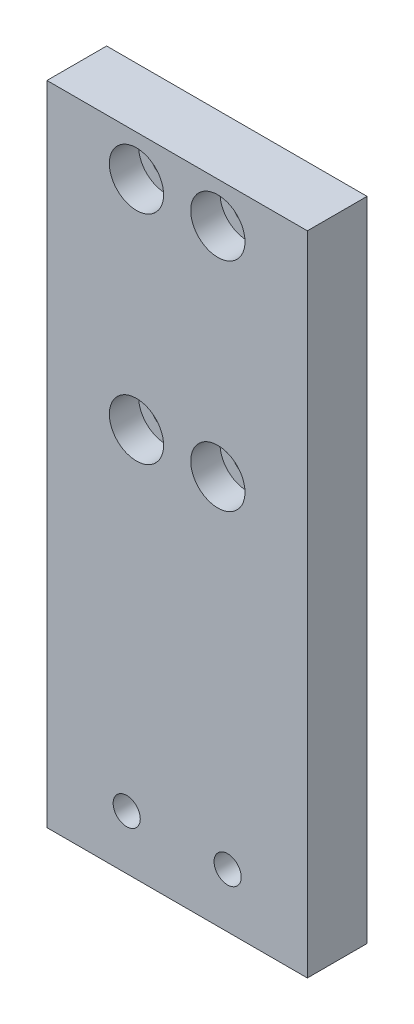
SolidWorks part; units mm, degrees
ref_plane "前视基准面" through (0, 0, 0) normal (0, 0, 1) x (1, 0, 0)
ref_plane "上视基准面" through (0, 0, 0) normal (0, 1, 0) x (1, 0, 0)
ref_plane "右视基准面" through (0, 0, 0) normal (1, 0, 0) x (0, 0, -1)
sketch "草图1" plane through (0, 0, 0) normal (0, 0, 1) x (1, 0, 0)
  line L0 (-129.6382, 0) -> (129.6107, 0) construction
  line L1 (0, 91.0608) -> (0, -96.972) construction
  line L3 (-24, 27.5) -> (24, 27.5)
  line L4 (-24, 27.5) -> (-24, -27.5)
  line L5 (-24, -27.5) -> (24, -27.5)
  line L6 (24, 27.5) -> (24, -27.5)
  dimension "D1" = 48
  dimension "D2" = 55
extrude "凸台-拉伸1" add sketch "草图1" along normal mid plane 11
hole_wizard "M5 六角凹头螺钉的柱形沉头孔1" positions "3D草图1" profile "草图3" counterbore size "M5" standard "Iso" end condition through all
sketch3d "3D草图1"
  point P0 (-7.5, -20, 5.5)
  dimension "D1" = 7.5
  dimension "D2" = 20
sketch "草图3" plane through (-7.5, -20, 5.5) normal (1, 0, 0) x (0, -1, 0)
  line L0 (0, 0) -> (0, 11)
  line L1 (0, 11) -> (2.75, 11)
  line L3 (2.75, 11) -> (2.75, 5.4)
  line L4 (2.75, 5.4) -> (5, 5.4)
  line L5 (5, 5.4) -> (5, 0)
  line L7 (5, 0) -> (0, 0)
  line L11 (0, -6.35) -> (0, 107.95) construction
  dimension "通孔孔直径" = 5.5
  dimension "通孔孔深度" = 11
  dimension "柱形沉头孔直径" = 10
  dimension "柱形沉头孔深度" = 5.4
mirror "镜向1" about plane through (0, 0, 0) normal (1, 0, 0) of "M5 六角凹头螺钉的柱形沉头孔1"
mirror "镜向2" about plane through (0, 0, 0) normal (0, 1, 0) of "镜向1", "M5 六角凹头螺钉的柱形沉头孔1"
sketch "草图4" plane through (0, -27.5, 0) normal (0, -1, 0) x (1, 0, 0)
  line L0 (-24, 5.5) -> (-24, -5.5)
  line L1 (-24, -5.5) -> (24, -5.5)
  line L2 (24, -5.5) -> (24, 5.5)
  line L3 (24, 5.5) -> (-24, 5.5)
extrude "凸台-拉伸2" add sketch "草图4" along normal blind 64.2772
sketch "草图5" plane through (0, 0, 5.5) normal (0, 0, 1) x (1, 0, 0)
  line L0 (24, -91.7772) -> (-24, -91.7772) construction
  line L1 (-24, 27.5) -> (-24, -91.7772) construction
  circle A0 centre (-9.3, -81.7772) radius 2.5
  circle A1 centre (9.3, -81.7772) radius 2.5
  dimension "D1" = 5
  dimension "D2" = 5
  dimension "D3" = 10
  dimension "D4" = 18.6
  dimension "D5" = 14.7
extrude "切除-拉伸1" cut sketch "草图5" against normal through all contours A0 | A1
